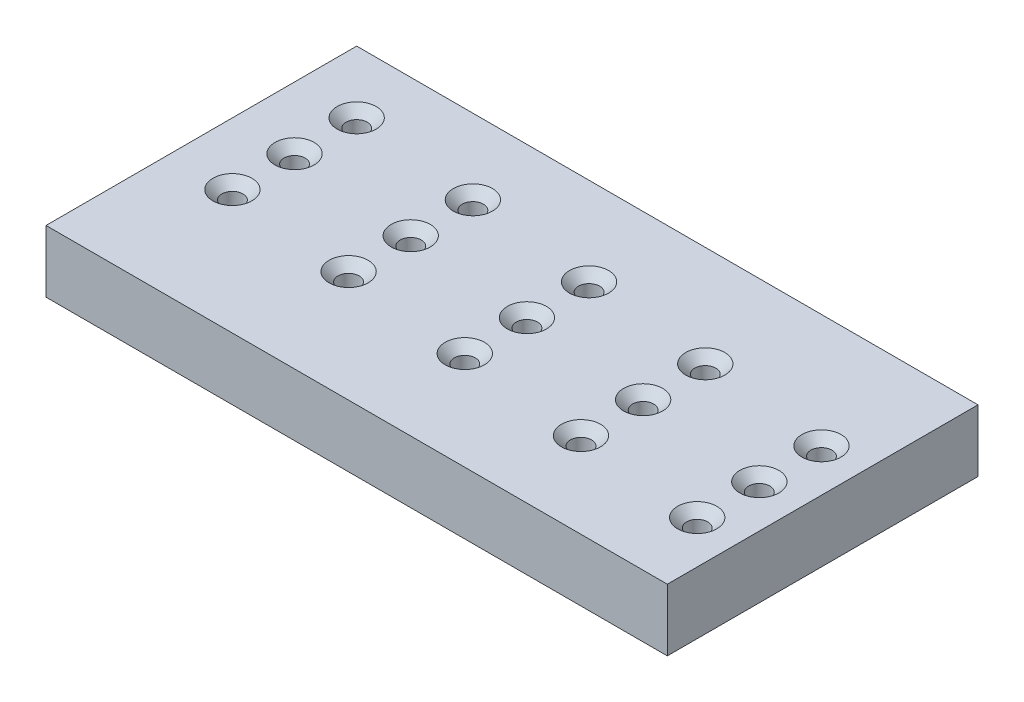
SolidWorks part; units mm, degrees
ref_plane "Front Plane" through (0, 0, 0) normal (0, 0, 1) x (1, 0, 0)
ref_plane "Top Plane" through (0, 0, 0) normal (0, 1, 0) x (1, 0, 0)
ref_plane "Right Plane" through (0, 0, 0) normal (1, 0, 0) x (0, 0, -1)
sketch "Sketch1" plane through (0, 0, 0) normal (0, 1, 0) x (1, 0, 0)
  line L0 (-50, 0) -> (0, 0) construction
  line L1 (-50, 25) -> (50, 25)
  line L2 (-50, 25) -> (-50, -25)
  line L3 (-50, -25) -> (50, -25)
  line L4 (50, 25) -> (50, -25)
  line L5 (0, 0) -> (0, 25) construction
  line L6 (0, 25) -> (0, 24.9) construction
  point P7 (0, 0)
  point P10 (0, 0)
  point P11 (0, 24.9)
  dimension "D1" = 50
  dimension "D2" = 100
extrude "Boss-Extrude1" add sketch "Sketch1" along normal blind 10
sketch "Sketch2" plane through (0, 10, 0) normal (0, 1, 0) x (1, 0, 0)
  line L0 (-50, 15) -> (-40, 15) construction
  line L1 (-50, 25) -> (-50, -25) construction
  line L2 (-40, 15) -> (-40, 25) construction
  line L3 (50, 25) -> (-50, 25) construction
  point P0 (-40, 15)
  dimension "D1" = 10
  dimension "D2" = 10
hole_wizard "CSK for M3 Flat Head Machine Screw1" positions "3DSketch1" profile "Sketch3" countersink size "M3" standard "ANSI Metric" end condition through all
sketch3d "3DSketch1"
  point P0 (-40, 10, -15)
sketch "Sketch3" plane through (-40, 10, -15) normal (1, 0, 0) x (0, 0, 1)
  line L0 (0, 0) -> (0, 10)
  line L1 (0, 10) -> (1.7, 10)
  line L2 (1.7, 10) -> (1.7, 1.45)
  line L3 (1.7, 1.45) -> (3.15, 0)
  line L5 (3.15, 0) -> (0, 0)
  line L6 (-1.7, 1.45) -> (-3.15, 0) construction
  line L11 (0, -6.35) -> (0, 107.95) construction
  dimension "Thru Hole Dia." = 3.4
  dimension "Thru Hole Depth" = 10
  dimension "Near C'Sink Dia." = 6.3
  dimension "Near C'Sink Angle" = 90
sketch "Sketch4" plane through (0, 10, 0) normal (0, 1, 0) x (1, 0, 0)
  line L0 (-50, 25) -> (50, 15) construction
  line L1 (50, -25) -> (50, 25) construction
  dimension "D1" = 10
pattern_linear "LPattern1" count 5 spacing 20.8834 along (0.995, 0, 0.0995) count 3 spacing 10 along (0, 0, 1) of "CSK for M3 Flat Head Machine Screw1"
